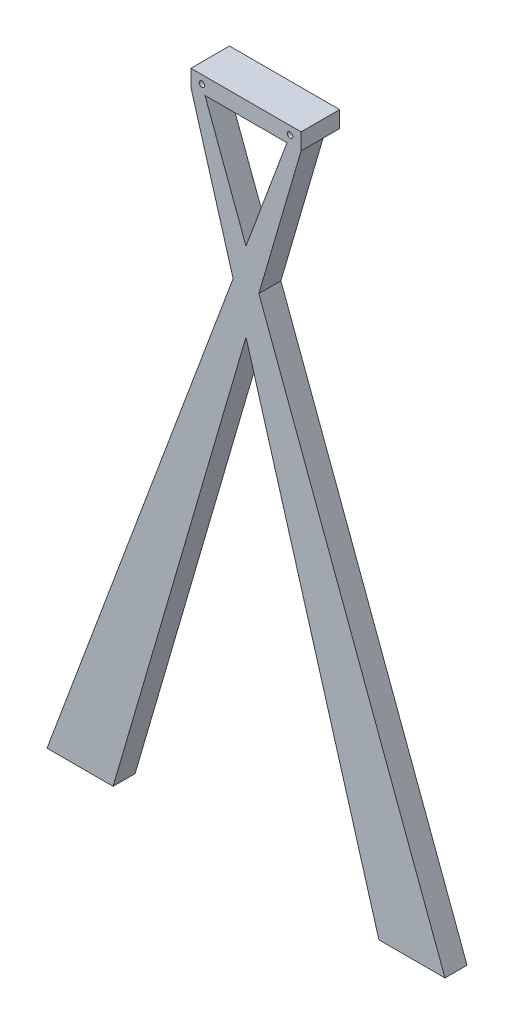
SolidWorks part; units mm, degrees
ref_plane "Front Plane" through (0, 0, 0) normal (0, 0, 1) x (1, 0, 0)
ref_plane "Top Plane" through (0, 0, 0) normal (0, 1, 0) x (1, 0, 0)
ref_plane "Right Plane" through (0, 0, 0) normal (1, 0, 0) x (0, 0, -1)
sketch "Sketch1" plane through (0, 0, 0) normal (0, 0, 1) x (1, 0, 0)
  line L0 (6.5342, 29.625) -> (11.5342, 29.625) construction
  line L1 (0, 0) -> (18.0683, 0)
  line L2 (0, 0) -> (0, 30)
  line L3 (0, 30) -> (18.0683, 30)
  line L4 (18.0683, 0) -> (18.0683, 30)
  line L5 (6.5342, 30) -> (11.5342, 30)
  line L6 (6.5342, 30) -> (6.5342, 29.25)
  line L7 (6.5342, 29.25) -> (11.5342, 29.25)
  line L8 (11.5342, 30) -> (11.5342, 29.25)
  line L9 (9.0342, 30) -> (9.0342, 29.25) construction
  line L10 (7.0342, 29.625) -> (18.0683, 0)
  line L11 (11.0342, 29.625) -> (0, 0)
  line L12 (11.5342, 28.9879) -> (11.5342, 29.25)
  line L13 (6.5342, 29.25) -> (15.0683, 0)
  line L14 (11.5342, 29.25) -> (3, 0)
  circle A0 centre (7.0342, 29.625) radius 0.125
  circle A1 centre (11.0342, 29.625) radius 0.125
  dimension "D3" = 0.25
  dimension "D4" = 0.25
  dimension "D6" = 2
  dimension "D1" = 5
  dimension "D2" = 0.75
  dimension "D5" = 2
  dimension "D7" = 30
  dimension "D8" = 3
  dimension "D9" = 3
extrude "Boss-Extrude1" add sketch "Sketch1" along normal blind 1
scale "Scale1" bodies to scale 101 scale about centroid uniform scaling yes scale factor 25.399986
sketch "Sketch2" plane through (0, 0, -12.2) normal (0, 0, -1) x (-1, 0, 0)
  line L1 (-72.5341, 472.5364) -> (54.4658, 472.5364)
  line L2 (-72.5341, 472.5364) -> (-72.5341, 453.4864)
  line L3 (-72.5341, 453.4864) -> (54.4658, 453.4864)
  line L4 (54.4658, 472.5364) -> (54.4658, 453.4864)
  circle A0 centre (-59.8341, 463.0114) radius 3.175
  circle A1 centre (41.7658, 463.0114) radius 3.175
  point P12 (0, 0)
extrude "Boss-Extrude2" add sketch "Sketch2" along normal blind 19.05 contours L2 L1 L4 L3 | A1 | A0
